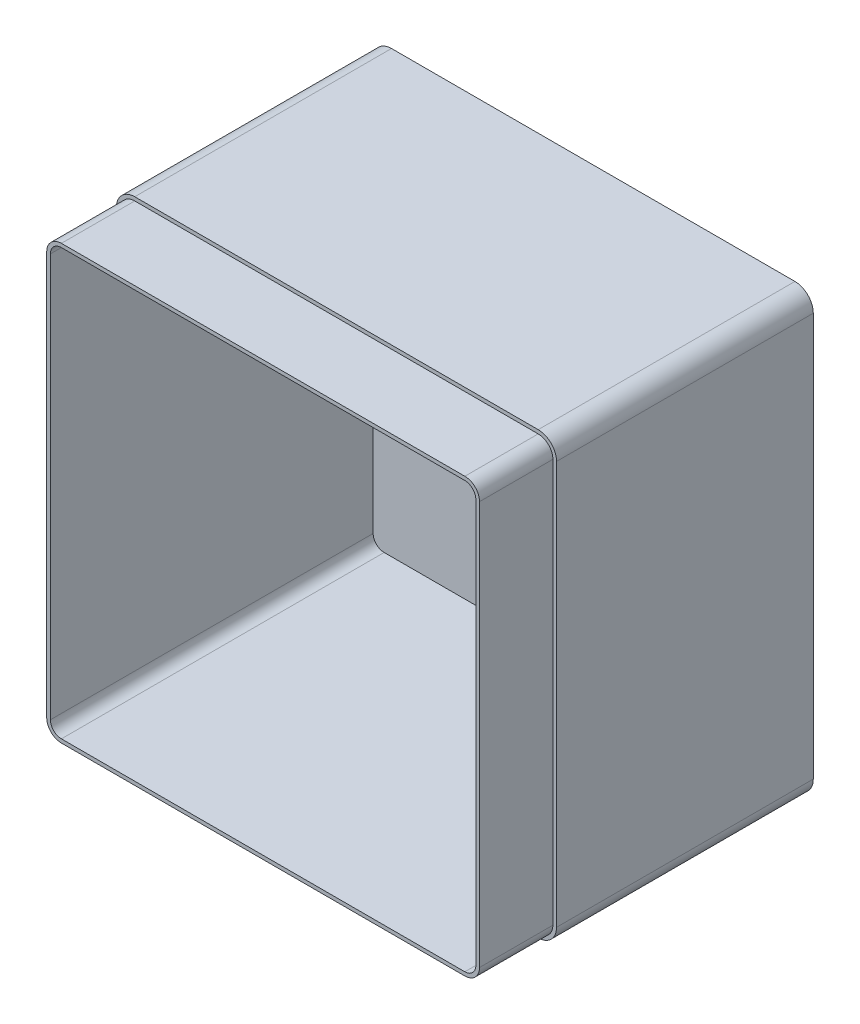
SolidWorks part; units mm, degrees
ref_plane "Plan de face" through (0, 0, 0) normal (0, 0, 1) x (1, 0, 0)
ref_plane "Plan de dessus" through (0, 0, 0) normal (0, 1, 0) x (1, 0, 0)
ref_plane "Plan de droite" through (0, 0, 0) normal (1, 0, 0) x (0, 0, -1)
sketch "Esquisse1" plane through (0, 0, 0) normal (0, 0, 1) x (1, 0, 0)
  line L1 (0, 0) -> (120, 0)
  line L2 (0, 0) -> (0, 120)
  line L3 (0, 120) -> (120, 120)
  line L4 (120, 0) -> (120, 120)
  dimension "D1" = 120
  dimension "D2" = 120
extrude "Boss.-Extru.1" add sketch "Esquisse1" along normal blind 90
fillet "Congé1" radius 5 4 edges at (0, 0, 45) (120, 0, 45) (0, 120, 45) (120, 120, 45)
shell "Coque1" thickness 2
sketch "Esquisse4" plane through (0, 0, 90) normal (0, 0, 1) x (1, 0, 0)
  line L0 (1, 115) -> (1, 5)
  line L1 (5, 1) -> (115, 1)
  line L2 (119, 5) -> (119, 115)
  line L3 (115, 119) -> (5, 119)
  line L4 (0, 115) -> (0, 5)
  line L5 (5, 0) -> (115, 0)
  line L6 (120, 5) -> (120, 115)
  line L7 (115, 120) -> (5, 120)
  line L8 (0, 115) -> (0, 5)
  line L9 (5, 0) -> (115, 0)
  line L10 (120, 5) -> (120, 115)
  line L11 (115, 120) -> (5, 120)
  arc A0 (1, 5) -> (5, 1) centre (5, 5) ccw
  arc A1 (115, 1) -> (119, 5) centre (115, 5) ccw
  arc A2 (119, 115) -> (115, 119) centre (115, 115) ccw
  arc A3 (5, 119) -> (1, 115) centre (5, 115) ccw
  arc A4 (0, 5) -> (5, 0) centre (5, 5) ccw
  arc A5 (115, 0) -> (120, 5) centre (115, 5) ccw
  arc A6 (120, 115) -> (115, 120) centre (115, 115) ccw
  arc A7 (5, 120) -> (0, 115) centre (5, 115) ccw
  arc A8 (0, 5) -> (5, 0) centre (5, 5) ccw
  arc A9 (115, 0) -> (120, 5) centre (115, 5) ccw
  arc A10 (120, 115) -> (115, 120) centre (115, 115) ccw
  arc A11 (5, 120) -> (0, 115) centre (5, 115) ccw
  dimension "D1" = 0
  dimension "D2" = 1
extrude "Enlèv. mat.-Extru.2" cut sketch "Esquisse4" against normal blind 20
